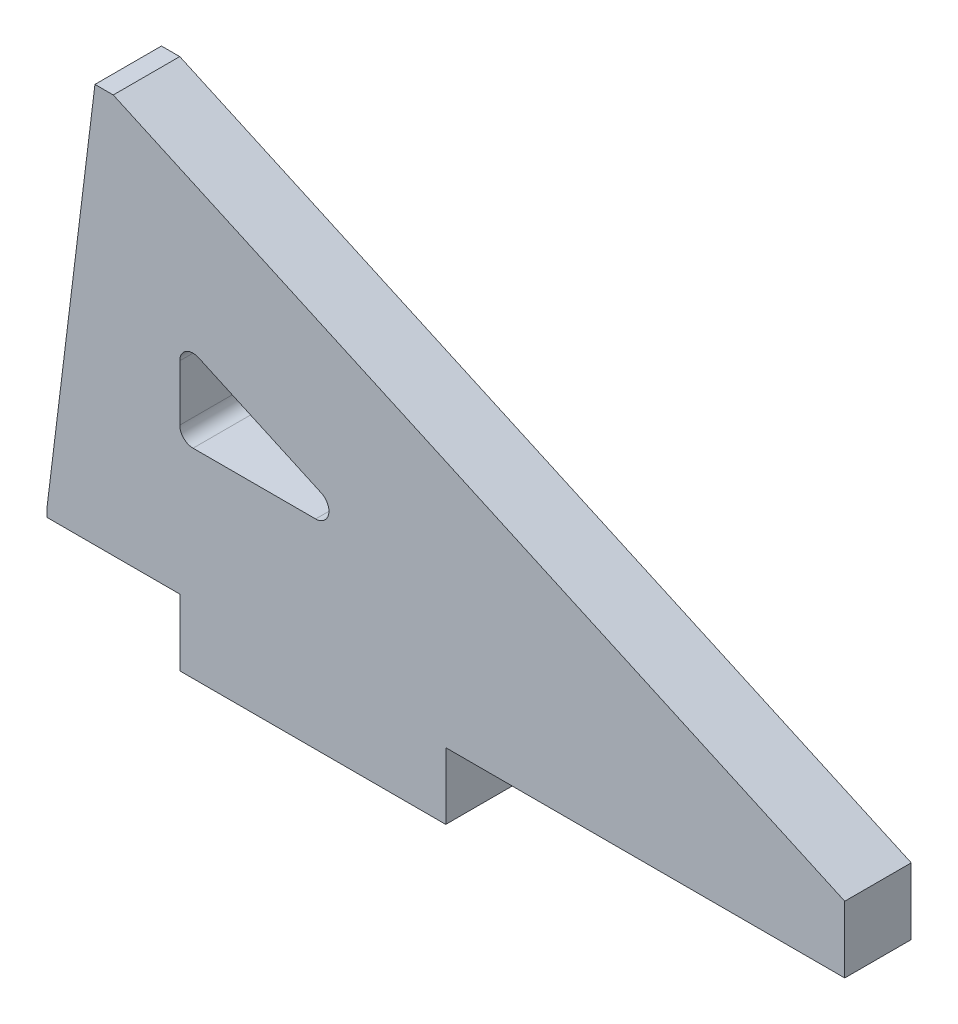
SolidWorks part; units mm, degrees
ref_plane "Front Plane" through (0, 0, 0) normal (0, 0, 1) x (1, 0, 0)
ref_plane "Top Plane" through (0, 0, 0) normal (0, 1, 0) x (1, 0, 0)
ref_plane "Right Plane" through (0, 0, 0) normal (1, 0, 0) x (0, 0, -1)
sketch "Sketch2" plane through (0, 0, 0) normal (0, 0, 1) x (1, 0, 0)
  line L0 (0, 0) -> (0, 6.35)
  line L1 (0, 6.35) -> (-12.7, 6.35)
  line L2 (-12.7, 6.35) -> (-12.7, 44.45)
  line L3 (-12.7, 44.45) -> (-6.35, 44.45)
  line L4 (-6.35, 44.45) -> (63.5, 12.7)
  line L5 (63.5, 12.7) -> (63.5, 6.35)
  line L6 (63.5, 6.35) -> (25.4, 6.35)
  line L7 (25.4, 6.35) -> (25.4, 0)
  line L8 (25.4, 0) -> (0, 0)
  line L9 (0, 25.6409) -> (0, 20.32)
  line L10 (1.27, 19.05) -> (12.976, 19.05)
  line L11 (13.5015, 21.4762) -> (1.7955, 26.7971)
  arc A0 (0, 20.32) -> (1.27, 19.05) centre (1.27, 20.32) ccw
  arc A1 (12.976, 19.05) -> (13.5015, 21.4762) centre (12.976, 20.32) ccw
  arc A2 (1.7955, 26.7971) -> (0, 25.6409) centre (1.27, 25.6409) ccw
  dimension "D11" = 1.27
  dimension "D1" = 6.35
  dimension "D2" = 25.4
  dimension "D3" = 12.7
  dimension "D4" = 38.1
  dimension "D5" = 6.35
  dimension "D6" = 38.1
  dimension "D7" = 6.35
  dimension "D8" = 12.7
  dimension "D9" = 12.7
  dimension "D10" = 12.7
extrude "Boss-Extrude1" add sketch "Sketch2" along normal blind 6.35
sketch "Sketch3" plane through (0, 0, 6.35) normal (0, 0, 1) x (1, 0, 0)
  line L1 (-5.0375, 69.3767) -> (-15.8717, -18.8607) construction
  line L2 (-8.0981, 44.45) -> (-12.7, 6.9706)
  line L12 (0, 0) -> (25.4, 0)
  line L13 (25.4, 0) -> (25.4, 6.35)
  line L14 (25.4, 6.35) -> (63.5, 6.35)
  line L15 (63.5, 6.35) -> (63.5, 12.7)
  line L16 (63.5, 12.7) -> (-6.35, 44.45)
  line L17 (-6.35, 44.45) -> (-12.7, 44.45)
  line L18 (-12.7, 44.45) -> (-12.7, 6.35)
  line L19 (-12.7, 6.35) -> (0, 6.35)
  line L20 (0, 6.35) -> (0, 0)
  line L26 (-8.0981, 44.45) -> (-12.7, 44.45)
  line L27 (-12.7, 44.45) -> (-12.7, 6.9706)
  dimension "D1" = 0
extrude "Cut-Extrude1" cut sketch "Sketch3" against normal through all
